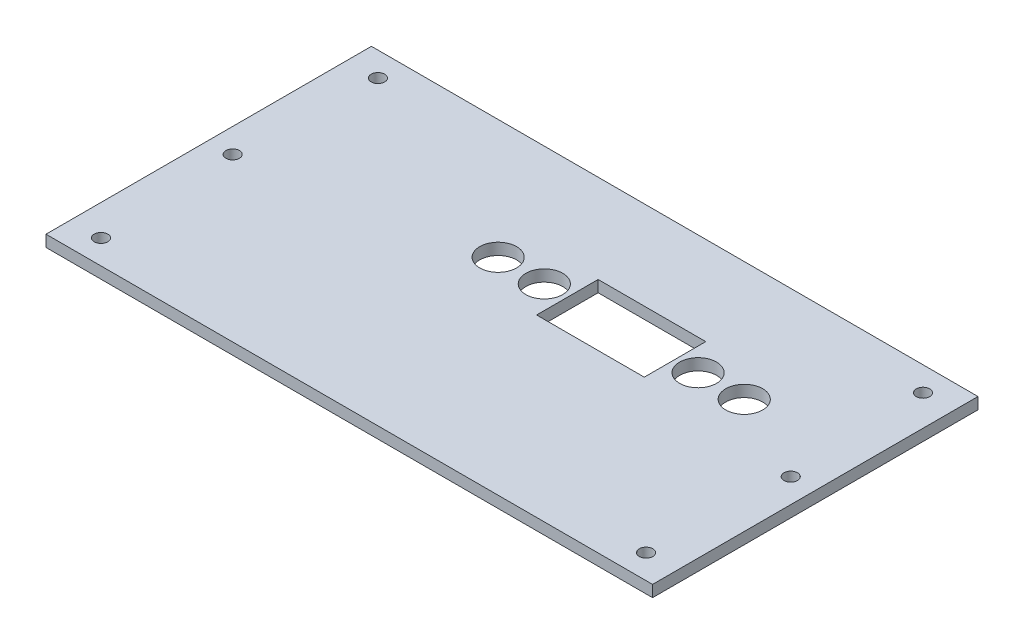
SolidWorks part; units mm, degrees
material "Acrylic (Medium-high impact)"
ref_plane "Front Plane" through (0, 0, 0) normal (0, 0, 1) x (1, 0, 0)
ref_plane "Top Plane" through (0, 0, 0) normal (0, 1, 0) x (1, 0, 0)
ref_plane "Right Plane" through (0, 0, 0) normal (1, 0, 0) x (0, 0, -1)
sketch "Sketch1" plane through (0, 0, 0) normal (0, 1, 0) x (1, 0, 0)
  line L0 (-50.8, 0) -> (50.8, 0) construction
  line L1 (-22.225, 12.7) -> (22.225, 12.7)
  line L2 (-22.225, 12.7) -> (-22.225, -12.7)
  line L3 (-22.225, -12.7) -> (22.225, -12.7)
  line L4 (22.225, 12.7) -> (22.225, -12.7)
  line L5 (0, 12.7) -> (0, -12.7) construction
  line L7 (-152.4, 49.276) -> (98.044, 49.276)
  line L8 (-152.4, 49.276) -> (-152.4, -85.09)
  line L9 (-152.4, -85.09) -> (98.044, -85.09)
  line L10 (98.044, 49.276) -> (98.044, -85.09)
  circle A0 centre (-50.8, 0) radius 7.62
  circle A1 centre (-31.75, 0) radius 7.62
  circle A2 centre (31.75, 0) radius 7.62
  circle A3 centre (50.8, 0) radius 7.62
  circle A4 centre (-139.7, 39.2684) radius 2.794
  circle A5 centre (85.344, 39.2684) radius 2.794
  circle A6 centre (88.0364, -18.034) radius 2.794
  circle A7 centre (85.344, -75.0824) radius 2.794
  circle A8 centre (-139.7, -75.0824) radius 2.794
  circle A9 centre (-142.3924, -18.034) radius 2.794
  dimension "D1" = 15.24
  dimension "D2" = 15.24
  dimension "D3" = 15.24
  dimension "D4" = 15.24
  dimension "D16" = 5.588
  dimension "D17" = 5.588
  dimension "D18" = 5.588
  dimension "D19" = 5.588
  dimension "D20" = 5.588
  dimension "D21" = 5.588
  dimension "D5" = 19.05
  dimension "D6" = 19.05
  dimension "D7" = 63.5
  dimension "D8" = 31.75
  dimension "D9" = 44.45
  dimension "D10" = 25.4
  dimension "D11" = 12.7
  dimension "D12" = 134.366
  dimension "D13" = 101.6
  dimension "D14" = 85.09
  dimension "D15" = 47.244
  dimension "D22" = 10.0076
  dimension "D23" = 12.7
  dimension "D24" = 10.0076
  dimension "D25" = 12.7
  dimension "D26" = 10.0076
  dimension "D27" = 67.31
  dimension "D28" = 10.0076
  dimension "D29" = 10.0076
  dimension "D30" = 12.7
  dimension "D31" = 12.7
  dimension "D32" = 10.0076
  dimension "D33" = 67.31
extrude "Boss-Extrude1" add sketch "Sketch1" along normal blind 4.7625
